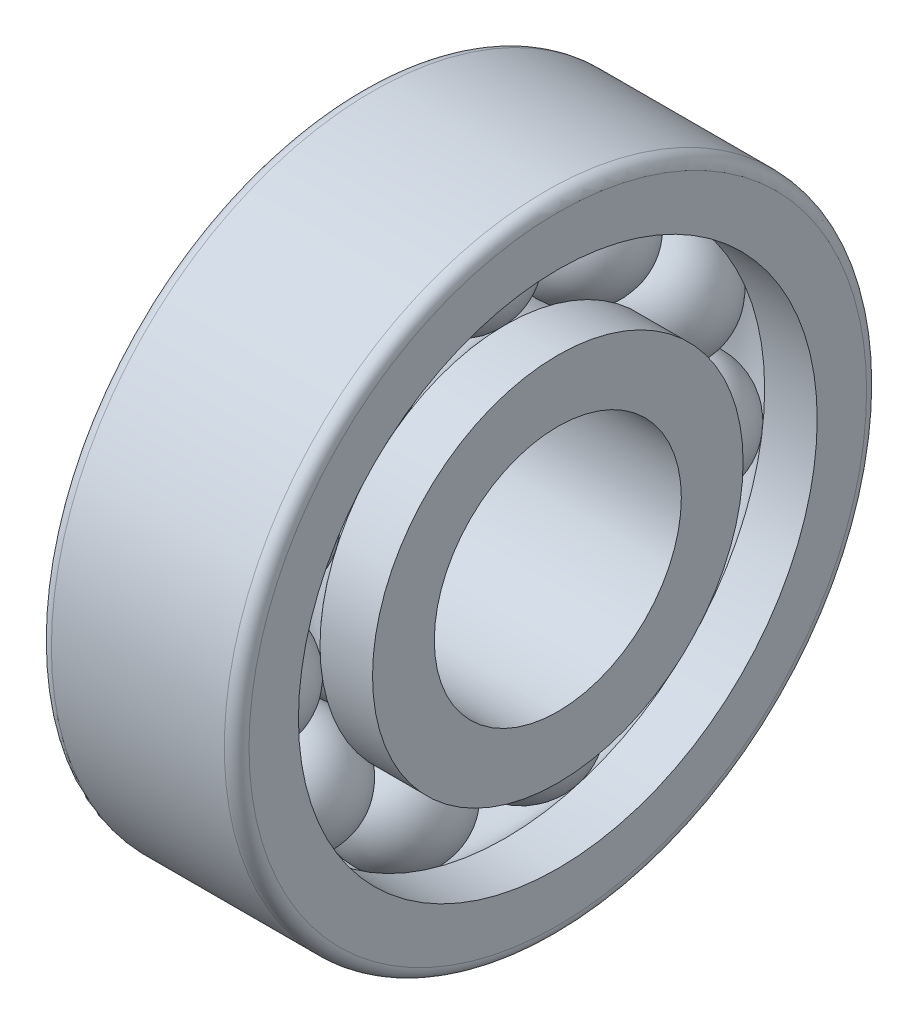
SolidWorks part; units mm, degrees
ref_plane "Plan de face" through (0, 0, 0) normal (0, 0, 1) x (1, 0, 0)
ref_plane "Plan de dessus" through (0, 0, 0) normal (0, 1, 0) x (1, 0, 0)
ref_plane "Plan de droite" through (0, 0, 0) normal (1, 0, 0) x (0, 0, -1)
sketch "Esquisse1" plane through (0, 0, 0) normal (0, 0, 1) x (1, 0, 0)
  line L0 (0, 0) -> (-106.0421, 0) construction
  line L1 (0, 10.5) -> (0, 13)
  line L2 (0, 13) -> (-8, 13)
  line L3 (-8, 13) -> (-8, 10.5)
  line L4 (-2.1265, 10.5) -> (0, 10.5)
  line L5 (0, 0) -> (0, 5)
  line L6 (-8, 10.5) -> (-5.8735, 10.5)
  line L7 (0, 5) -> (-8, 5)
  line L8 (-8, 5) -> (-8, 7.5)
  line L9 (-8, 7.5) -> (-5.8735, 7.5)
  line L10 (0, 7.5) -> (0, 5)
  line L11 (-2.1265, 7.5) -> (0, 7.5)
  arc A0 (-2.1265, 10.5) -> (-5.8735, 10.5) centre (-4, 9) ccw
  arc A1 (-5.8735, 7.5) -> (-2.1265, 7.5) centre (-4, 9) ccw
  arc A2 (-2.1265, 10.5) -> (-5.8735, 10.5) centre (-4, 9) ccw
  dimension "D1" = 8
revolve "Révolution1" add sketch "Esquisse1" angle 360 about L0
sketch "Esquisse2" plane through (0, 0, 0) normal (0, 0, 1) x (1, 0, 0)
  line L2 (-1.6, 9) -> (-4, 9)
  line L3 (-4, 9) -> (-6.4, 9)
  line L4 (-7.5952, 9) -> (0.9356, 9) construction
  arc A0 (-1.6, 9) -> (-6.4, 9) centre (-4, 9) ccw
revolve "Révolution2" add sketch "Esquisse2" angle 360 about L4
pattern_circular "Répétition circulaire1" count 11 over 360 about axis through (0, 0, 0) along (1, 0, 0) of bodies 103
fillet "Congé1" radius 0.5 2 edges at (-8, 0, -13) (0, 0, -13)
